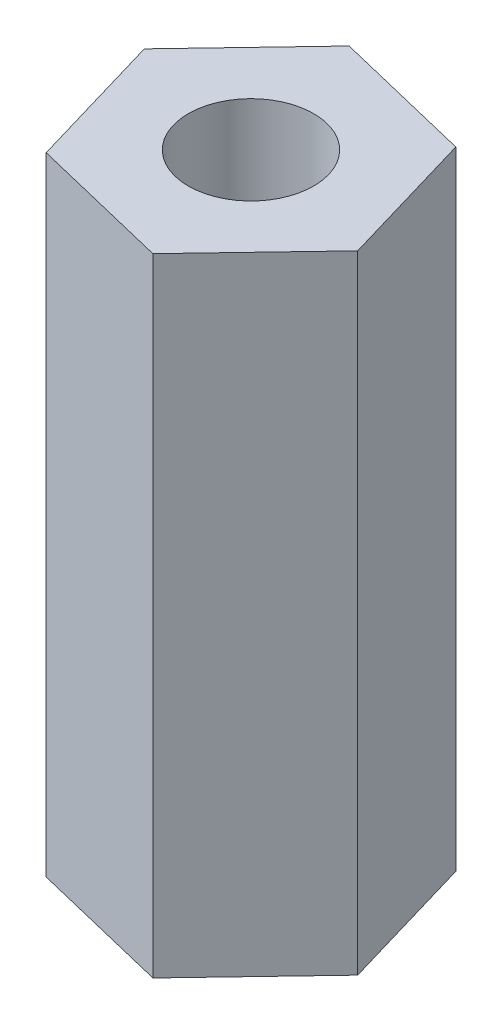
SolidWorks part; units mm, degrees
material "Thornel VCB-20 Carbon Cloth"
ref_plane "Front Plane" through (0, 0, 0) normal (0, 0, 1) x (1, 0, 0)
ref_plane "Top Plane" through (0, 0, 0) normal (0, 1, 0) x (1, 0, 0)
ref_plane "Right Plane" through (0, 0, 0) normal (1, 0, 0) x (0, 0, -1)
sketch "Sketch1" plane through (0, 0, 0) normal (0, 1, 0) x (1, 0, 0)
  line L1 (0.9773, -3.3234) -> (3.3668, -0.8153)
  line L2 (3.3668, -0.8153) -> (2.3895, 2.508)
  line L3 (2.3895, 2.508) -> (-0.9773, 3.3234)
  line L4 (-0.9773, 3.3234) -> (-3.3668, 0.8153)
  line L5 (-3.3668, 0.8153) -> (-2.3895, -2.508)
  line L6 (-2.3895, -2.508) -> (0.9773, -3.3234)
  circle A0 centre (0, 0) radius 1.5
  circle A1 centre (0, 0) radius 3 construction
  dimension "D1" = 3
  dimension "D2" = 6
extrude "Boss-Extrude1" add sketch "Sketch1" along normal mid plane 15
